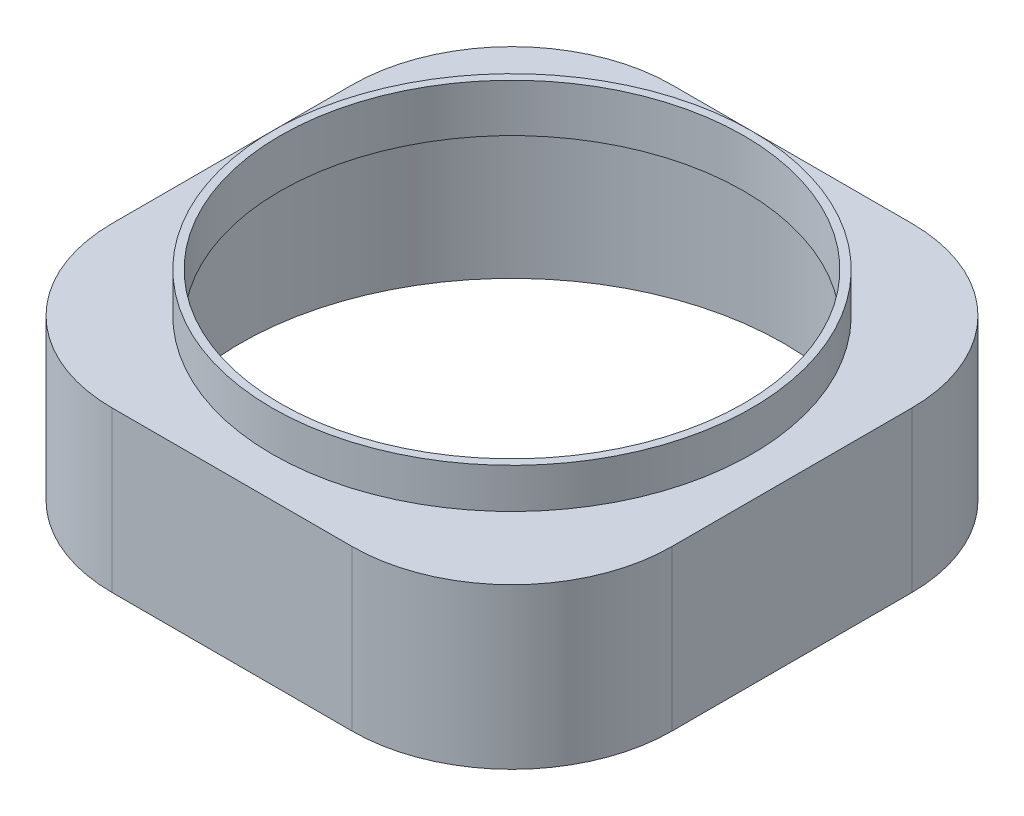
SolidWorks part; units mm, degrees
ref_plane "Front Plane" through (0, 0, 0) normal (0, 0, 1) x (1, 0, 0)
ref_plane "Top Plane" through (0, 0, 0) normal (0, 1, 0) x (1, 0, 0)
ref_plane "Right Plane" through (0, 0, 0) normal (1, 0, 0) x (0, 0, -1)
sketch "Sketch1" plane through (0, 0, 0) normal (0, 1, 0) x (1, 0, 0)
  line L1 (-30, 70) -> (30, 70)
  line L2 (-70, 30) -> (-70, -30)
  line L3 (-30, -70) -> (30, -70)
  line L4 (70, 30) -> (70, -30)
  arc A0 (-30, -70) -> (-70, -30) centre (-30, -30) cw
  arc A1 (30, -70) -> (70, -30) centre (30, -30) ccw
  arc A2 (70, 30) -> (30, 70) centre (30, 30) ccw
  arc A3 (-70, 30) -> (-30, 70) centre (-30, 30) cw
  dimension "D1" = 40
extrude "Boss-Extrude1" add sketch "Sketch1" against normal blind 40
sketch "Sketch2" plane through (0, 0, 0) normal (0, 1, 0) x (1, 0, 0)
  circle A0 centre (0, 0) radius 60
extrude "Boss-Extrude2" add sketch "Sketch2" along normal blind 10
sketch "Sketch3" plane through (0, 10, 0) normal (0, 1, 0) x (1, 0, 0)
  circle A0 centre (0, 0) radius 58
extrude "Cut-Extrude1" cut sketch "Sketch3" against normal blind 12
sketch "Sketch5" plane through (0, -40, 0) normal (0, -1, 0) x (1, 0, 0)
  circle A4 centre (0, 0) radius 68
extrude "Cut-Extrude3" cut sketch "Sketch5" against normal blind 38 contours A4
